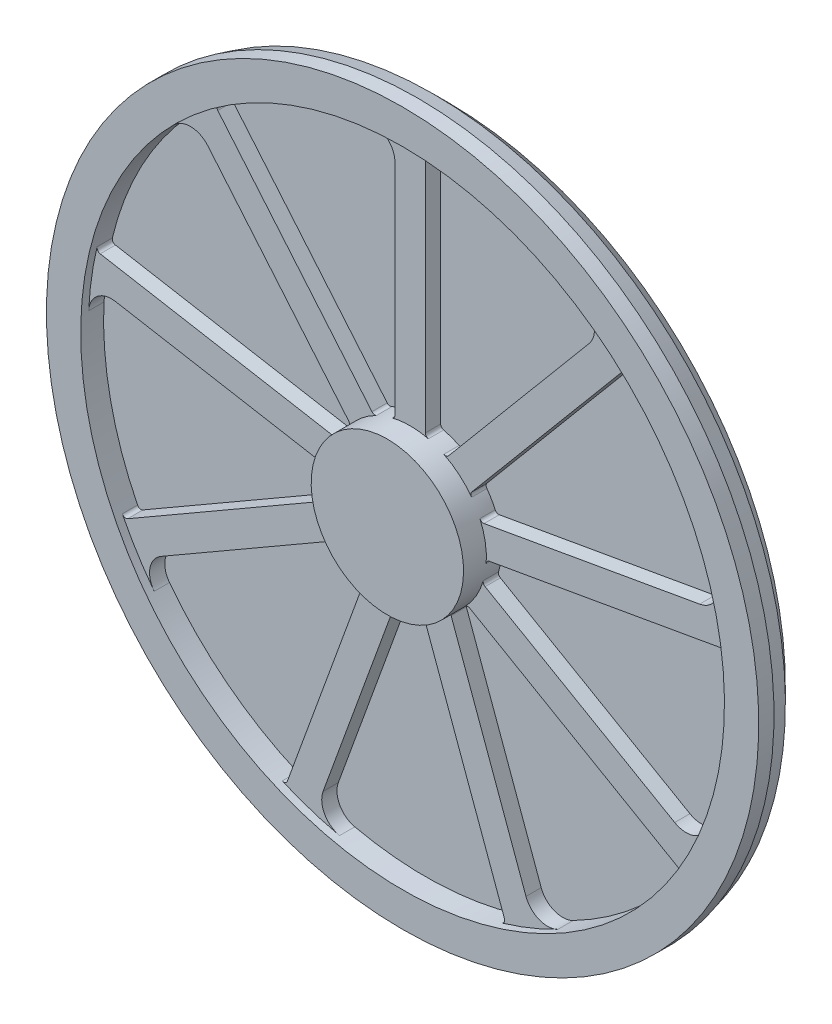
SolidWorks part; units mm, degrees
material "1060 Alloy"
ref_plane "Front Plane" through (0, 0, 0) normal (0, 0, 1) x (1, 0, 0)
ref_plane "Top Plane" through (0, 0, 0) normal (0, 1, 0) x (1, 0, 0)
ref_plane "Right Plane" through (0, 0, 0) normal (1, 0, 0) x (0, 0, -1)
sketch "Sketch1" plane through (0, 0, 0) normal (1, 0, 0) x (0, 0, -1)
  line L0 (0, -565.0706) -> (0, 565.0706) construction
  line L1 (-371.6129, 0) -> (371.6129, 0) construction
  line L2 (-50, 0) -> (-50, 100)
  line L3 (-50, 100) -> (0, 100)
  line L4 (0, 100) -> (0, 422.5)
  line L5 (0, 422.5) -> (-30, 422.5)
  line L6 (-30, 422.5) -> (-30, 467.5)
  line L7 (-30, 467.5) -> (-10, 467.5)
  line L8 (-10, 467.5) -> (10.4904, 462.0096)
  line L9 (10.4904, 462.0096) -> (30, 442.5)
  line L10 (30, 442.5) -> (30, 0)
  line L11 (30, 0) -> (-50, 0)
  point P1 (0, 0)
  point P4 (0, 0)
  point P8 (0, 0)
  point P25 (0, 0)
  dimension "D2" = 80
  dimension "D3" = 200
  dimension "D4" = 885
  dimension "D5" = 935
  dimension "D6" = 60
  dimension "D7" = 20
  dimension "D8" = 15
  dimension "D9" = 45
  dimension "D11" = 30
  dimension "D12" = 45
revolve "Revolve2" add sketch "Sketch1" angle 360 about L11
sketch "Sketch2" plane through (0, 0, 0) normal (0, 0, 1) x (1, 0, 0)
  line L0 (283.2032, 306.3939) -> (80.8726, 65.2658)
  line L1 (20, 416.7508) -> (20, 101.9804)
  line L2 (-20, 389.3023) -> (-20, 101.9804)
  line L3 (234.9178, 311.0786) -> (50.2308, 90.9773)
  line L4 (413.8924, 52.6719) -> (103.904, -1.9874)
  line L5 (379.9149, 87.2978) -> (96.9581, 37.4049)
  line L6 (350.9168, -225.6959) -> (78.3176, -68.3107)
  line L7 (347.1456, -177.3306) -> (98.3176, -33.6697)
  line L8 (123.7433, -398.4581) -> (16.0855, -102.6706)
  line L9 (151.9431, -358.9841) -> (53.6732, -88.9898)
  line L10 (-161.331, -384.7773) -> (-53.6732, -88.9898)
  line L11 (-114.3554, -372.6649) -> (-16.0855, -102.6706)
  line L12 (-370.9168, -191.0549) -> (-98.3176, -33.6697)
  line L13 (-327.1456, -211.9716) -> (-78.3176, -68.3107)
  line L14 (-406.9465, 92.0642) -> (-96.9581, 37.4049)
  line L15 (-386.8608, 47.9055) -> (-103.904, -1.9874)
  line L16 (-252.5614, 332.1054) -> (-50.2308, 90.9773)
  line L17 (-265.5596, 285.3671) -> (-80.8726, 65.2658)
  circle A0 centre (25, 101.9804) radius 5
  circle A1 centre (0, 0) radius 100 construction
  circle A2 centre (0, 0) radius 422.5 construction
  arc A3 (-20, 389.3023) -> (-53.8217, 419.0578) centre (-50, 389.3023) ccw
  arc A4 (25.2994, 421.7419) -> (20, 416.7508) centre (25, 416.7508) ccw
  arc A5 (-23.8095, 97.1242) -> (-20, 101.9804) centre (-25, 101.9804) ccw
  circle A6 centre (84.7028, 62.0518) radius 5
  arc A7 (234.9178, 311.0786) -> (228.1354, 355.6128) centre (211.9364, 330.3622) ccw
  arc A8 (290.4709, 306.8109) -> (283.2032, 306.3939) centre (287.0334, 303.18) ccw
  arc A9 (44.1911, 89.7059) -> (50.2308, 90.9773) centre (46.4006, 94.1912) ccw
  circle A10 centre (104.7723, -6.9115) radius 5
  arc A11 (379.9149, 87.2978) -> (403.3454, 125.7726) centre (374.7055, 116.842) ccw
  arc A12 (419.7278, 48.3197) -> (413.8924, 52.6719) centre (414.7606, 47.7478) ccw
  arc A13 (91.5142, 40.3132) -> (96.9581, 37.4049) centre (96.0899, 42.3289) ccw
  circle A14 centre (75.8176, -72.6408) radius 5
  arc A15 (347.1456, -177.3306) -> (389.8256, -162.918) centre (362.1456, -151.3499) ccw
  arc A16 (352.5895, -232.7809) -> (350.9168, -225.6959) centre (348.4168, -230.026) ccw
  arc A17 (96.0168, -27.9424) -> (98.3176, -33.6697) centre (100.8176, -29.3396) ccw
  circle A18 centre (11.387, -104.3807) radius 5
  arc A19 (151.9431, -358.9841) -> (193.902, -375.3775) centre (180.1338, -348.7235) ccw
  arc A20 (120.4705, -404.9606) -> (123.7433, -398.4581) centre (119.0449, -400.1682) ccw
  arc A21 (55.5921, -83.1235) -> (53.6732, -88.9898) centre (58.3717, -87.2797) ccw
  circle A22 centre (-58.3717, -87.2797) radius 5
  arc A23 (-114.3554, -372.6649) -> (-92.7504, -412.1937) centre (-86.1646, -382.9255) ccw
  arc A24 (-168.0179, -387.6548) -> (-161.331, -384.7773) centre (-166.0295, -383.0672) ccw
  arc A25 (-10.8448, -99.4102) -> (-16.0855, -102.6706) centre (-11.387, -104.3807) ccw
  circle A26 centre (-100.8176, -29.3396) radius 5
  arc A27 (-327.1456, -211.9716) -> (-336.0039, -256.1398) centre (-312.1456, -237.9524) ccw
  arc A28 (-377.8889, -188.961) -> (-370.9168, -191.0549) centre (-373.4168, -186.7248) ccw
  arc A29 (-72.2072, -69.1817) -> (-78.3176, -68.3107) centre (-75.8176, -72.6408) ccw
  circle A30 centre (-96.0899, 42.3289) radius 5
  arc A31 (-386.8608, 47.9055) -> (-422.0374, 19.7646) centre (-392.0703, 18.3612) ccw
  arc A32 (-410.9415, 98.1498) -> (-406.9465, 92.0642) centre (-406.0782, 96.9882) ccw
  arc A33 (-99.7831, -6.5824) -> (-103.904, -1.9874) centre (-104.7723, -6.9115) ccw
  circle A34 centre (-46.4006, 94.1912) radius 5
  arc A35 (-265.5596, 285.3671) -> (-310.595, 286.421) centre (-288.5409, 266.0835) ccw
  arc A36 (-251.71, 339.3351) -> (-252.5614, 332.1054) centre (-248.7312, 335.3193) ccw
  arc A37 (-80.6694, 59.097) -> (-80.8726, 65.2658) centre (-84.7028, 62.0518) ccw
  point P5 (0, 0)
  point P9 (20, 259.3656)
  point P23 (182.0379, 185.8298)
  point P36 (258.8982, 25.3422)
  point P49 (214.6172, -147.0033)
  point P62 (69.9144, -250.5644)
  point P75 (-107.5021, -236.8835)
  point P88 (-234.6172, -112.3623)
  point P101 (-251.9523, 64.7345)
  point P114 (-151.3961, 211.5413)
  point P123 (0, 0)
  circle M6 centre (0, 0) radius 100
  circle M7 centre (0, 0) radius 422.5
  dimension "D1" = 40
  dimension "D2" = 845
  dimension "D4" = 60
  dimension "D5" = 10
  dimension "D6" = 10
  dimension "D3" = 200
  dimension "D7" = 10
  dimension "D8" = 314.7704
  dimension "D9" = 9
extrude "Boss-Extrude2" add sketch "Sketch2" along normal blind 20 contours A5 A0 L1 A4 A3 L2 M6 M7 | A9 A6 L0 A8 A7 L3 M6 M7 | A13 A10 L4 A12 A11 L5 M6 M7 | A37 A34 L16 A36 A35 L17 M6 M7 | A33 A30 L14 A32 A31 L15 M6 M7 | A29 A26 L12 A28 A27 L13 M6 M7 | A25 A22 L10 A24 A23 L11 M6 M7 | A21 A18 L8 A20 A19 L9 M6 M7 | A17 A14 L6 A16 A15 L7 M6 M7
